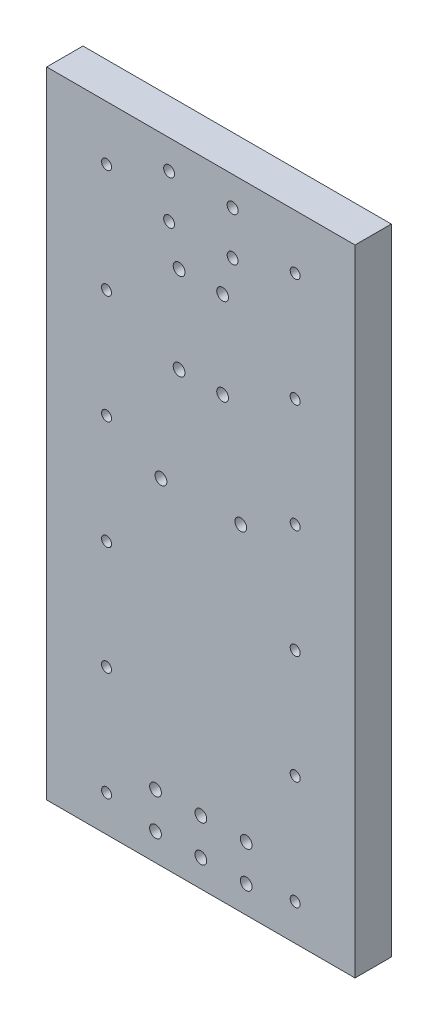
SolidWorks part; units mm, degrees
material "3.3547 (EN-AW 5083)"
ref_plane "Ebene vorne" through (0, 0, 0) normal (0, 0, 1) x (1, 0, 0)
ref_plane "Ebene oben" through (0, 0, 0) normal (0, 1, 0) x (1, 0, 0)
ref_plane "Ebene rechts" through (0, 0, 0) normal (1, 0, 0) x (0, 0, -1)
sketch "Skizze1" plane through (0, 0, 0) normal (0, 0, 1) x (1, 0, 0)
  line L0 (0, 0) -> (0, 467.2939) construction
  line L2 (-85, 0) -> (85, 0)
  line L3 (-85, 0) -> (-85, 350)
  line L4 (-85, 350) -> (85, 350)
  line L5 (85, 0) -> (85, 350)
  dimension "D1" = 350
  dimension "D2" = 170
extrude "Aufsatz-Linear austragen1" add sketch "Skizze1" along normal blind 20
sketch "Skizze4" plane through (0, 0, 0) normal (0, 0, -1) x (-1, 0, 0)
  line L0 (0, 0) -> (0, 341.6165) construction
  line L1 (17.5, 334) -> (17.5, 310) construction
  line L2 (-85, 350) -> (85, 350) construction
  circle A0 centre (17.5, 334) radius 3
  circle A1 centre (17.5, 310) radius 3
  circle A2 centre (-17.5, 310) radius 3
  circle A3 centre (-17.5, 334) radius 3
  dimension "D4" = 6
  dimension "D1" = 35
  dimension "D2" = 16
  dimension "D3" = 24
extrude "Schnitt-Linear austragen3" cut sketch "Skizze4" against normal blind 30
sketch "Skizze5" plane through (0, 0, 20) normal (0, 0, 1) x (1, 0, 0)
  line L0 (0, 0) -> (0, 259.5762) construction
  line L1 (-85, 0) -> (85, 0) construction
  circle A0 centre (52, 20) radius 2.75
  circle A1 centre (-52, 20) radius 2.75
  dimension "D1" = 104
  dimension "D2" = 20
  dimension "D3" = 5.5
extrude "Schnitt-Linear austragen4" cut sketch "Skizze5" against normal blind 50
pattern_linear "Lineares Muster1" count 6 spacing 60 along (0, 1, 0) of "Schnitt-Linear austragen4"
sketch "Skizze6" plane through (0, 0, 20) normal (0, 0, 1) x (1, 0, 0)
  line L0 (0, 0) -> (0, 15) construction
  line L1 (0, 15) -> (25, 15) construction
  line L2 (-85, 0) -> (85, 0) construction
  line L3 (-40.5676, 25) -> (45.3561, 25) construction
  circle A0 centre (0, 15) radius 3.25
  circle A1 centre (25, 15) radius 3.25
  circle A2 centre (-25, 15) radius 3.25
  circle A3 centre (25, 35) radius 3.25
  circle A4 centre (0, 35) radius 3.25
  circle A5 centre (-25, 35) radius 3.25
  dimension "D1" = 50
  dimension "D2" = 6.5
  dimension "D3" = 15
  dimension "D4" = 10
  dimension "D5" = 35
extrude "Schnitt-Linear austragen5" cut sketch "Skizze6" against normal blind 40
sketch "Skizze7" plane through (0, 0, 20) normal (0, 0, 1) x (1, 0, 0)
  line L0 (0, 0) -> (0, 357.5949) construction
  line L1 (52, 320) -> (52, 260) construction
  line L2 (52, 290) -> (0, 290) construction
  line L3 (12, 290) -> (12, 242) construction
  circle A0 centre (12, 290) radius 3.25
  circle A1 centre (-12, 290) radius 3.25
  circle A2 centre (12, 242) radius 3.25
  circle A3 centre (-12, 242) radius 3.25
  circle A4 centre (22, 185) radius 3.25
  circle A5 centre (-22, 185) radius 3.25
  dimension "D1" = 24
  dimension "D2" = 6.5
  dimension "D4" = 44
  dimension "D5" = 57
  dimension "D3" = 48
extrude "Schnitt-Linear austragen6" cut sketch "Skizze7" against normal blind 50
